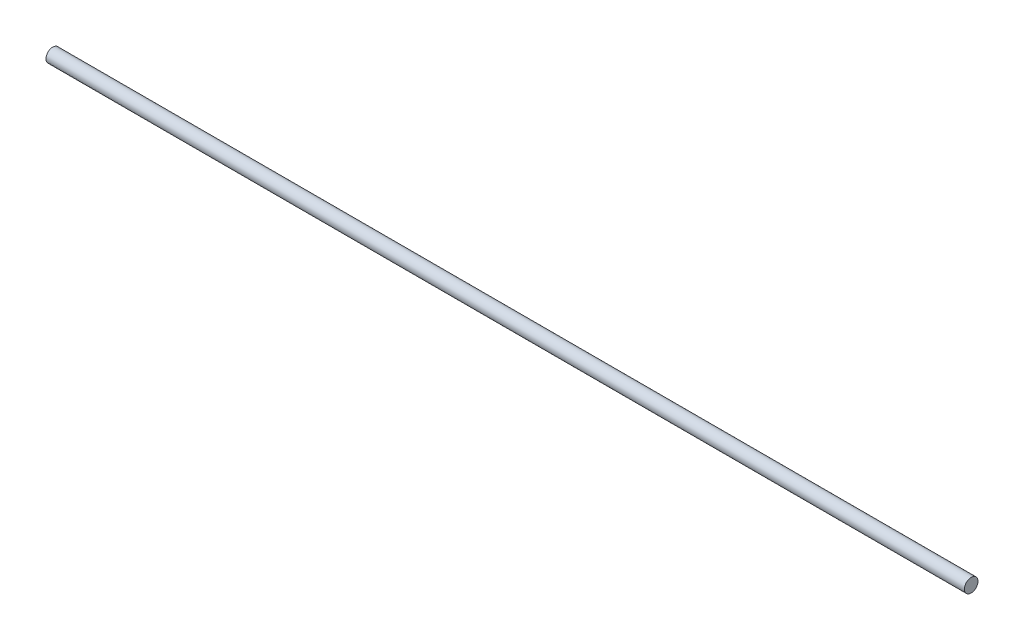
SolidWorks part; units mm, degrees
material "AISI 4340 Steel, annealed"
ref_plane "Front Plane" through (0, 0, 0) normal (0, 0, 1) x (1, 0, 0)
ref_plane "Top Plane" through (0, 0, 0) normal (0, 1, 0) x (1, 0, 0)
ref_plane "Right Plane" through (0, 0, 0) normal (1, 0, 0) x (0, 0, -1)
sketch "Sketch1" plane through (0, 0, 0) normal (1, 0, 0) x (0, 0, -1)
  circle A0 centre (0, 0) radius 5
  dimension "D1" = 10
extrude "Boss-Extrude1" add sketch "Sketch1" along normal mid plane 676 contours A0
